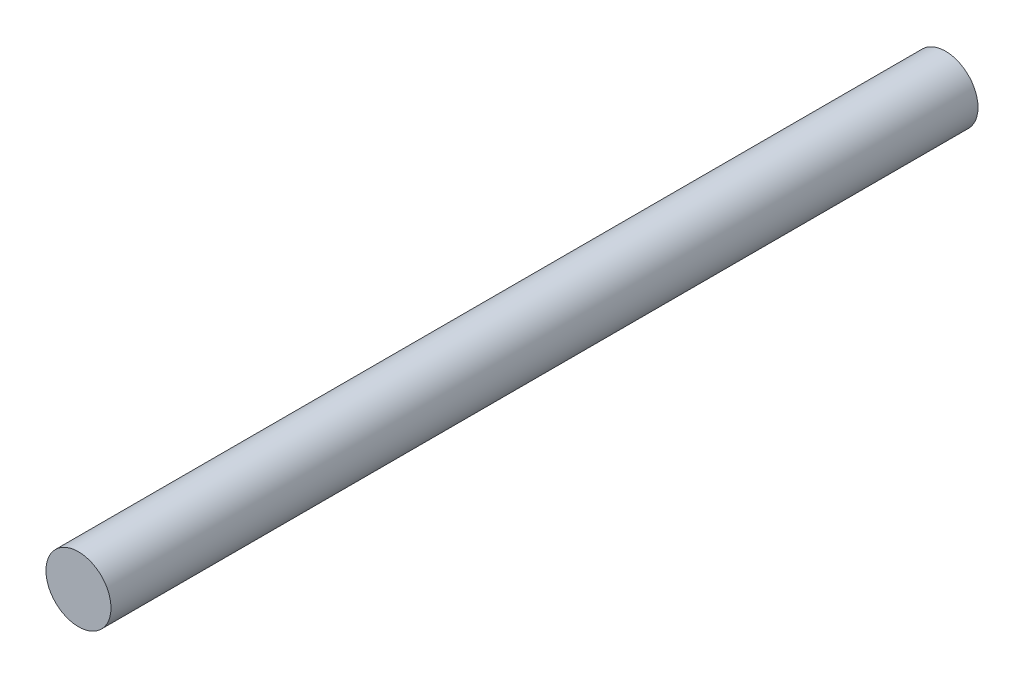
SolidWorks part; units mm, degrees
ref_plane "Front Plane" through (0, 0, 0) normal (0, 0, 1) x (1, 0, 0)
ref_plane "Top Plane" through (0, 0, 0) normal (0, 1, 0) x (1, 0, 0)
ref_plane "Right Plane" through (0, 0, 0) normal (1, 0, 0) x (0, 0, -1)
sketch "Sketch1" plane through (0, 0, 0) normal (0, 0, 1) x (1, 0, 0)
  circle A0 centre (0, 0) radius 4.7625
  dimension "D1" = 9.525
extrude "Boss-Extrude1" add sketch "Sketch1" along normal blind 127
